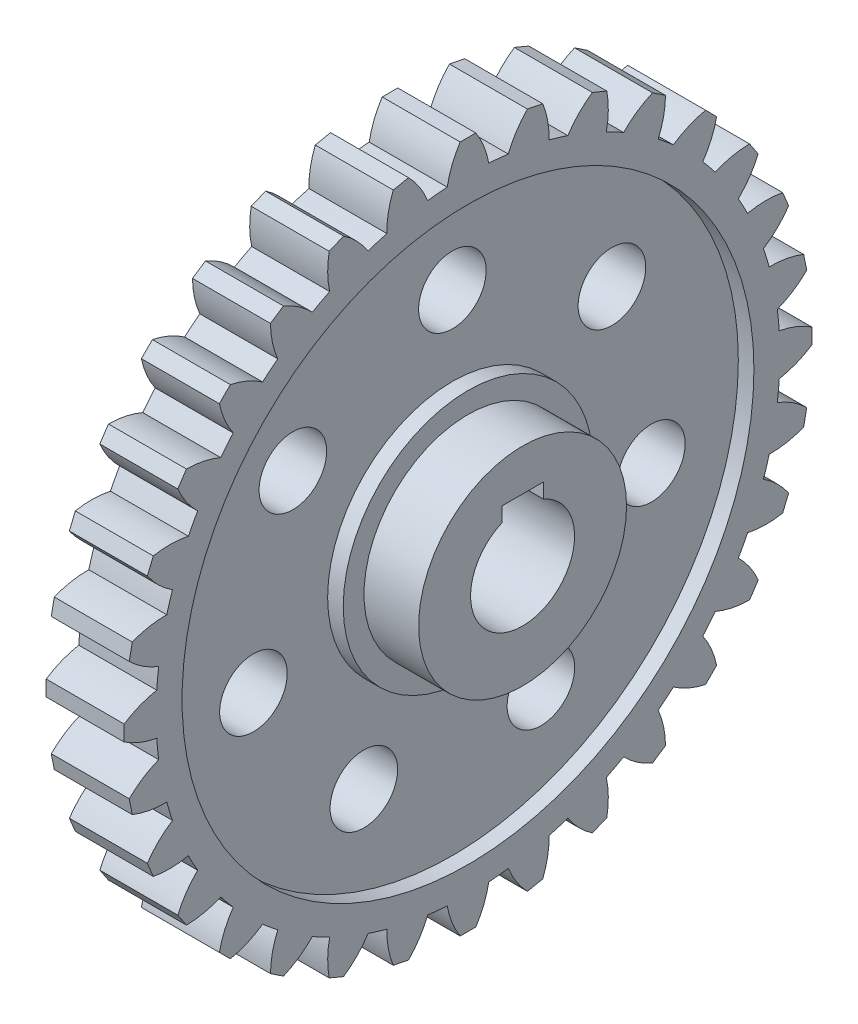
SolidWorks part; units mm, degrees
ref_plane "Front Plane" through (0, 0, 0) normal (0, 0, 1) x (1, 0, 0)
ref_plane "Top Plane" through (0, 0, 0) normal (0, 1, 0) x (1, 0, 0)
ref_plane "Right Plane" through (0, 0, 0) normal (1, 0, 0) x (0, 0, -1)
sketch "Sketch1" plane through (0, 0, 0) normal (1, 0, 0) x (0, 0, -1)
  circle A0 centre (0, 0) radius 60
  dimension "D1" = 120
extrude "Boss-Extrude1" add sketch "Sketch1" along normal mid plane 15
sketch "Sketch2" plane through (7.5, 0, 0) normal (1, 0, 0) x (0, 0, -1)
  line L0 (0, 0) -> (0, 81.9271) construction
  line L1 (-1.5, 66.1365) -> (1.5, 66.1365)
  arc A0 (-4, 59.8665) -> (4, 59.8665) centre (0, 0) ccw
  circle A1 centre (0, 0) radius 60 construction
  arc A2 (-1.5, 66.1365) -> (-4, 59.8665) centre (12.7267, 56.8306) ccw
  arc A3 (1.5, 66.1365) -> (4, 59.8665) centre (-12.7267, 56.8306) cw
  dimension "D4" = 17
  dimension "D1" = 3
  dimension "D2" = 6.27
  dimension "D3" = 4
extrude "Boss-Extrude2" add sketch "Sketch2" against normal up to surface (15 mm away) up to face at (-7.5, 0, -60)
pattern_circular "CirPattern1" count 32 over 360 about axis through (0, 0, 0) along (1, 0, 0) of "Boss-Extrude2"
sketch "Sketch4" plane through (0, 0, 0) normal (1, 0, 0) x (0, 0, -1)
  circle A0 centre (0, 0) radius 20
extrude "Boss-Extrude4" add sketch "Sketch4" along normal mid plane 36
sketch "Sketch5" plane through (18, 0, 0) normal (1, 0, 0) x (0, 0, -1)
  line L0 (0, 0) -> (0, 15.5416) construction
  line L1 (-4, 12) -> (4, 12)
  line L2 (-4, 12) -> (-4, 9.1652)
  line L3 (4, 12) -> (4, 9.1652)
  arc A0 (-4, 9.1652) -> (4, 9.1652) centre (0, 0) ccw
  dimension "D1" = 8
  dimension "D2" = 12
extrude "Cut-Extrude1" cut sketch "Sketch5" against normal through all
sketch "Sketch6" plane through (7.5, 0, 0) normal (1, 0, 0) x (0, 0, -1)
  circle A0 centre (0, 0) radius 55
  circle A1 centre (0, 0) radius 24
extrude "Cut-Extrude2" cut sketch "Sketch6" against normal blind 3
sketch "Sketch7" plane through (4.5, 0, 0) normal (1, 0, 0) x (0, 0, -1)
  circle A0 centre (0, 0) radius 39.25 construction
  circle A1 centre (0, 39.25) radius 6.5
  circle A2 centre (30.6869, 24.472) radius 6.5
  circle A3 centre (38.2659, -8.7339) radius 6.5
  circle A4 centre (17.0299, -35.363) radius 6.5
  circle A5 centre (-17.0299, -35.363) radius 6.5
  circle A6 centre (-38.2659, -8.7339) radius 6.5
  circle A7 centre (-30.6869, 24.472) radius 6.5
  point P19 (0, 0)
  dimension "D1" = 78.5
  dimension "D2" = 13
  dimension "D3" = 7
extrude "Cut-Extrude3" cut sketch "Sketch7" against normal through all
